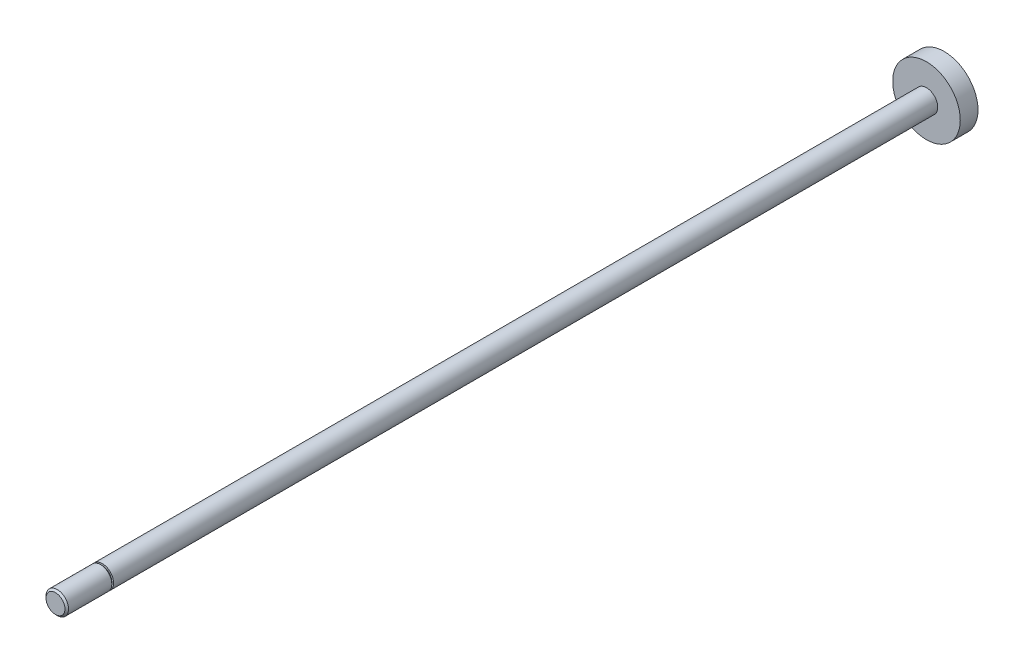
SolidWorks part; units mm, degrees
ref_plane "Front" through (0, 0, 0) normal (0, 0, 1) x (1, 0, 0)
ref_plane "Top" through (0, 0, 0) normal (0, 1, 0) x (1, 0, 0)
ref_plane "Right" through (0, 0, 0) normal (1, 0, 0) x (0, 0, -1)
sketch "Sketch1" plane through (0, 0, 0) normal (0, 0, 1) x (1, 0, 0)
  circle A0 centre (0, 0) radius 3.175
  dimension "MM" = 6.35
extrude "Extrude1" add sketch "Sketch1" along normal up to surface (248.031 mm away)
sketch "Sketch2" plane through (0, 0, 0) normal (0, 0, 1) x (1, 0, 0)
  circle A0 centre (0, 0) radius 9.525
  dimension "Bore" = 19.05
extrude "Piston" add sketch "Sketch2" along normal mid plane 5
sketch "Sketch3" plane through (0, 0, 0) normal (1, 0, 0) x (0, 0, -1)
  line L0 (-248.031, 9.525) -> (-234.831, 9.525)
  line L1 (-248.031, 9.525) -> (-248.031, 2.675)
  line L2 (-248.031, 2.675) -> (-247.531, 3.175)
  line L3 (-247.531, 3.175) -> (-235.331, 3.175)
  line L4 (-235.331, 3.175) -> (-235.331, 2.675)
  line L5 (-235.331, 2.675) -> (-234.831, 2.675)
  line L6 (-234.831, 2.675) -> (-234.831, 9.525)
  line L8 (-248.031, 3.175) -> (-248.031, -3.175) construction
  line L9 (2.5, 9.525) -> (-2.5, 9.525) construction
  line L10 (0, 0) -> (-105.1844, 0) construction
  dimension "D1" = 45
  dimension "KK" = 6.35
  dimension "D2" = 0.5
  dimension "D3" = 0.5
  dimension "D4" = 0.5
  dimension "A" = 12.7
revolve "Threads" cut sketch "Sketch3" angle 360 about L10
sketch "Sketch4" [suppressed] plane through (0, 0, 0) normal (0, 1, 0) x (1, 0, 0)
  line L0 (0, 0) -> (0, -104.7006) construction
  line L1 (7.9375, -174.879) -> (6.35, -174.879)
  line L2 (7.9375, -174.879) -> (-7.9375, -174.879) construction
  line L3 (6.35, -174.879) -> (6.35, -165.277)
  line L4 (6.35, -165.277) -> (7.9375, -163.6895)
  line L5 (7.9375, -163.6895) -> (7.9375, -174.879)
  line L6 (7.9375, -171.577) -> (7.9375, -2.5) construction
  line L7 (-7.9375, -163.6895) -> (-7.9375, -174.879)
  line L8 (-6.35, -165.277) -> (-7.9375, -163.6895)
  line L9 (-6.35, -174.879) -> (-6.35, -165.277)
  line L10 (-7.9375, -174.879) -> (-6.35, -174.879)
  dimension "D" = 6.35
  dimension "K" = 3.048
extrude "Flats" [suppressed] cut sketch "Sketch4" against normal through all and the other way through all
